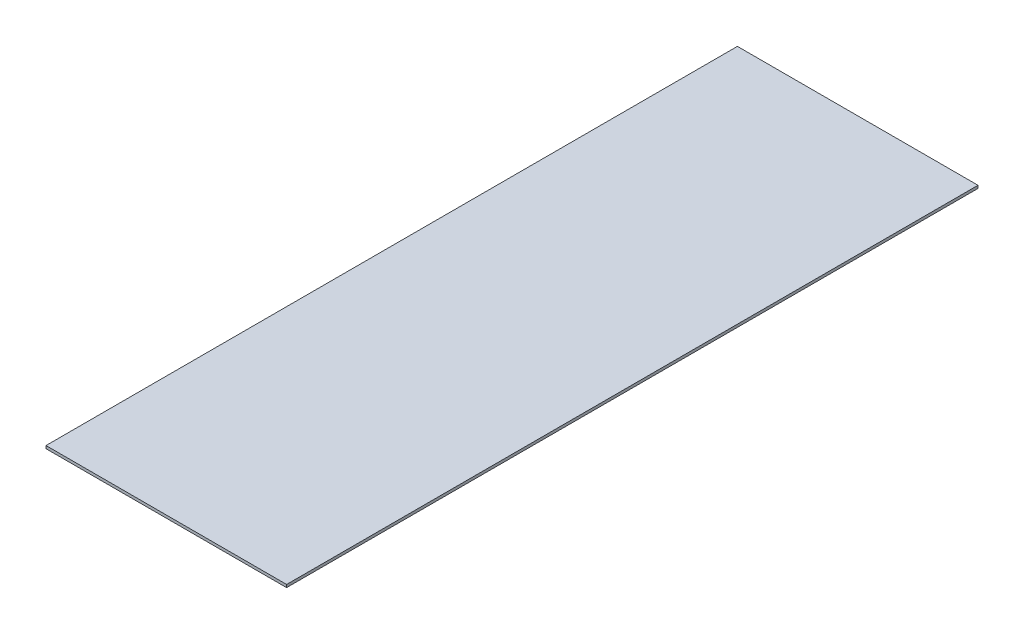
SolidWorks part; units mm, degrees
ref_plane "Front Plane" through (0, 0, 0) normal (0, 0, 1) x (1, 0, 0)
ref_plane "Top Plane" through (0, 0, 0) normal (0, 1, 0) x (1, 0, 0)
ref_plane "Right Plane" through (0, 0, 0) normal (1, 0, 0) x (0, 0, -1)
sketch "Sketch1" plane through (0, 0, 0) normal (0, 1, 0) x (1, 0, 0)
  line L0 (-174, 0) -> (-174, -500)
  line L1 (-174, -500) -> (0, -500)
  line L2 (0, -500) -> (0, 0)
  line L3 (0, 0) -> (-174, 0)
  dimension "D1" = 174
  dimension "D2" = 500
extrude "Boss-Extrude1" add sketch "Sketch1" along normal blind 2
equation "\"clip_tube_diam\"= 6mm"
equation "\"middle_tube_len\"= 500mm"
equation "\"horizontal_pipe_spacing\"= 260mm"
equation "\"belly_plate_width\" = 176mm"
equation "\"belly_bottom_width\" = 174mm"
equation "\"belly_length\"  = 500mm"
